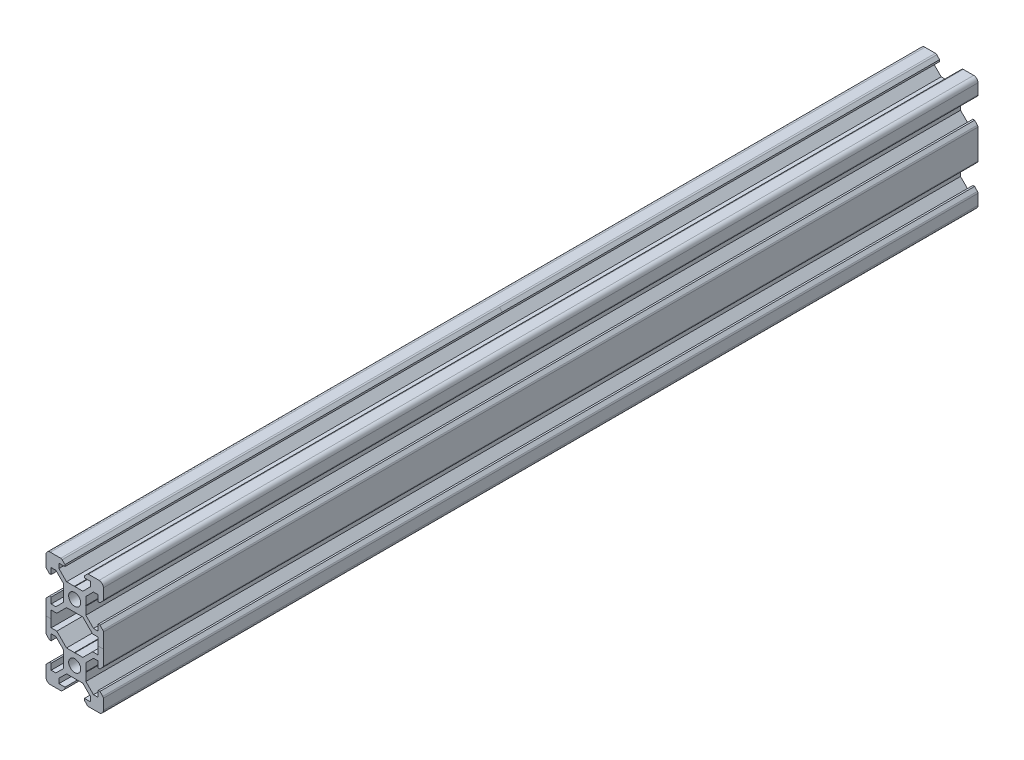
SolidWorks part; units mm, degrees
material "6063-T5"
ref_plane "Front" through (0, 0, 0) normal (0, 0, 1) x (1, 0, 0)
ref_plane "Top" through (0, 0, 0) normal (0, 1, 0) x (1, 0, 0)
ref_plane "Right" through (0, 0, 0) normal (1, 0, 0) x (0, 0, -1)
sketch "Sketch1" plane through (0, 0, 0) normal (0, 0, 1) x (1, 0, 0)
  line L0 (-8.5, 10) -> (-10, 8.5) construction
  line L1 (-8.5, 10) -> (-4.8628, 10)
  line L2 (-10, 8.5) -> (-10, 4.8628)
  line L4 (10, 8.5) -> (10, 4.8628)
  line L5 (-10, 10) -> (10, -10) construction
  line L6 (-10, -10) -> (10, 10) construction
  line L7 (8.2, -5.5) -> (8.2, -3.3865)
  line L8 (-8.2, -5.5) -> (-8.2, -3.3865)
  line L9 (-5.5, 8.2) -> (-3.3865, 8.2)
  line L10 (-8.2, -12.7) -> (-8.2, -7.3)
  line L11 (-3.9005, 2.8395) -> (-6.561, 5.5)
  line L12 (-6.561, 5.5) -> (-8.2, 5.5)
  line L13 (-2.8395, -3.9005) -> (-0.1, -3.9005)
  line L14 (-3.9005, -2.8395) -> (-3.9005, -0.1)
  line L15 (-2.8395, 3.9005) -> (-0.1, 3.9005)
  line L16 (3.9005, -2.8395) -> (3.9005, -0.1)
  line L17 (-8.2, 3.3865) -> (-8.81, 3.3865)
  line L18 (-8.81, 3.3865) -> (-9.7976, 4.3741)
  line L19 (8.5, 10) -> (10, 8.5) construction
  line L20 (-2.8395, 3.9005) -> (-5.5, 6.561)
  line L21 (-5.5, 6.561) -> (-5.5, 8.2)
  line L22 (-3.3865, 8.2) -> (-3.3865, 8.81)
  line L23 (-3.3865, 8.81) -> (-4.3741, 9.7976)
  line L24 (0, 24.069) -> (0, -33.8154) construction
  line L25 (3.3865, 8.81) -> (4.3741, 9.7976)
  line L26 (3.3865, 8.2) -> (3.3865, 8.81)
  line L27 (5.5, 6.561) -> (5.5, 8.2)
  line L28 (2.8395, 3.9005) -> (5.5, 6.561)
  line L29 (3.3865, 8.2) -> (5.5, 8.2)
  line L30 (4.8628, 10) -> (8.5, 10)
  line L31 (-0.1, 3.9005) -> (0, 3.8005)
  line L32 (0.1, 3.9005) -> (0, 3.8005)
  line L33 (0.1, 3.9005) -> (2.8395, 3.9005)
  line L34 (25.9287, 0) -> (-28.3459, 0) construction
  line L35 (-0.1, -3.9005) -> (0, -3.8005)
  line L36 (0.1, -3.9005) -> (0, -3.8005)
  line L37 (0.1, -3.9005) -> (2.8395, -3.9005)
  line L38 (-3.9005, 0.1) -> (-3.8005, 0)
  line L39 (-3.8005, 0) -> (-3.9005, -0.1)
  line L40 (-3.9005, 0.1) -> (-3.9005, 2.8395)
  line L41 (3.9005, 0.1) -> (3.8005, 0)
  line L42 (3.8005, 0) -> (3.9005, -0.1)
  line L43 (3.9005, 0.1) -> (3.9005, 2.8395)
  line L44 (8.81, 3.3865) -> (9.7976, 4.3741)
  line L45 (8.2, 3.3865) -> (8.81, 3.3865)
  line L46 (6.561, 5.5) -> (8.2, 5.5)
  line L47 (3.9005, 2.8395) -> (6.561, 5.5)
  line L48 (2.8395, -3.9005) -> (5.5, -6.561)
  line L49 (3.9005, -2.8395) -> (6.561, -5.5)
  line L50 (-2.8395, -3.9005) -> (-5.5, -6.561)
  line L51 (-3.9005, -2.8395) -> (-6.561, -5.5)
  line L52 (6.561, -5.5) -> (8.2, -5.5)
  line L53 (-6.561, -5.5) -> (-8.2, -5.5)
  line L54 (-8.81, -3.3865) -> (-9.7976, -4.3741)
  line L55 (-8.2, -3.3865) -> (-8.81, -3.3865)
  line L56 (8.81, -3.3865) -> (9.7976, -4.3741)
  line L57 (8.2, -3.3865) -> (8.81, -3.3865)
  line L58 (8.2, 3.3865) -> (8.2, 5.5)
  line L59 (10, -4.8628) -> (10, -15.1372)
  line L60 (-8.2, 3.3865) -> (-8.2, 5.5)
  line L61 (-10, -4.8628) -> (-10, -15.1372)
  line L62 (-28.3459, -10) -> (-10, -10) construction
  line L63 (-3.9005, -20.1) -> (-3.9005, -22.8395)
  line L64 (-3.9005, -20.1) -> (-3.8005, -20)
  line L65 (-3.8005, -20) -> (-3.9005, -19.9)
  line L66 (3.9005, -20.1) -> (3.9005, -22.8395)
  line L67 (3.9005, -20.1) -> (3.8005, -20)
  line L68 (3.8005, -20) -> (3.9005, -19.9)
  line L69 (6.561, -14.5) -> (8.2, -14.5)
  line L70 (3.9005, -17.1605) -> (6.561, -14.5)
  line L71 (3.9005, -17.1605) -> (3.9005, -19.9)
  line L72 (-3.9005, -17.1605) -> (-3.9005, -19.9)
  line L73 (-3.9005, -17.1605) -> (-6.561, -14.5)
  line L74 (-6.561, -14.5) -> (-8.2, -14.5)
  line L75 (-8.2, -16.6135) -> (-8.81, -16.6135)
  line L76 (-8.81, -16.6135) -> (-9.7976, -15.6259)
  line L77 (8.2, -16.6135) -> (8.81, -16.6135)
  line L78 (8.81, -16.6135) -> (9.7976, -15.6259)
  line L79 (-2.8395, -16.0995) -> (-5.5, -13.439)
  line L80 (-2.8395, -16.0995) -> (-0.1, -16.0995)
  line L81 (-0.1, -16.0995) -> (0, -16.1995)
  line L82 (0.1, -16.0995) -> (0, -16.1995)
  line L83 (0.1, -16.0995) -> (2.8395, -16.0995)
  line L84 (2.8395, -16.0995) -> (5.5, -13.439)
  line L85 (-8.2, -16.6135) -> (-8.2, -14.5)
  line L86 (8.2, -16.6135) -> (8.2, -14.5)
  line L87 (2.8395, -23.9005) -> (5.5, -26.561)
  line L88 (-2.8395, -23.9005) -> (-5.5, -26.561)
  line L89 (-0.1, -23.9005) -> (0, -23.8005)
  line L90 (0.1, -23.9005) -> (0, -23.8005)
  line L91 (0.1, -23.9005) -> (2.8395, -23.9005)
  line L92 (-2.8395, -23.9005) -> (-0.1, -23.9005)
  line L93 (-10, -28.5) -> (-10, -24.8628)
  line L94 (10, -28.5) -> (10, -24.8628)
  line L95 (8.81, -23.3865) -> (9.7976, -24.3741)
  line L96 (-8.81, -23.3865) -> (-9.7976, -24.3741)
  line L97 (-8.2, -23.3865) -> (-8.81, -23.3865)
  line L98 (8.2, -23.3865) -> (8.81, -23.3865)
  line L99 (8.2, -23.3865) -> (8.2, -25.5)
  line L100 (-8.2, -23.3865) -> (-8.2, -25.5)
  line L101 (-6.561, -25.5) -> (-8.2, -25.5)
  line L102 (6.561, -25.5) -> (8.2, -25.5)
  line L103 (3.9005, -22.8395) -> (6.561, -25.5)
  line L104 (-3.9005, -22.8395) -> (-6.561, -25.5)
  line L105 (-5.5, -28.2) -> (-3.3865, -28.2)
  line L106 (3.3865, -28.2) -> (5.5, -28.2)
  line L107 (3.3865, -28.2) -> (3.3865, -28.81)
  line L108 (3.3865, -28.81) -> (4.3741, -29.7976)
  line L109 (-3.3865, -28.2) -> (-3.3865, -28.81)
  line L110 (-3.3865, -28.81) -> (-4.3741, -29.7976)
  line L111 (-8.5, -30) -> (-4.8628, -30)
  line L112 (4.8628, -30) -> (8.5, -30)
  line L113 (-5.5, -26.561) -> (-5.5, -28.2)
  line L114 (5.5, -26.561) -> (5.5, -28.2)
  line L115 (-6.239, -7.3) -> (-8.2, -7.3)
  line L116 (-5.5, -6.561) -> (-6.239, -7.3)
  line L117 (6.239, -7.3) -> (8.2, -7.3)
  line L118 (5.5, -6.561) -> (6.239, -7.3)
  line L119 (-6.239, -12.7) -> (-8.2, -12.7)
  line L120 (-5.5, -13.439) -> (-6.239, -12.7)
  line L121 (5.5, -13.439) -> (6.239, -12.7)
  line L122 (6.239, -12.7) -> (8.2, -12.7)
  line L123 (8.2, -12.7) -> (8.2, -7.3)
  line L125 (10, -10) -> (25.9287, -10) construction
  circle A0 centre (0, 0) radius 2.1
  arc A1 (-8.5, 10) -> (-10, 8.5) centre (-8.5, 8.5) ccw
  arc A2 (10, 8.5) -> (8.5, 10) centre (8.5, 8.5) ccw
  arc A3 (-4.3741, 9.7976) -> (-4.8628, 10) centre (-4.8628, 9.3088) ccw
  arc A4 (4.8628, 10) -> (4.3741, 9.7976) centre (4.8628, 9.3088) ccw
  circle A5 centre (0, -20) radius 2.1
  arc A6 (9.7976, 4.3741) -> (10, 4.8628) centre (9.3088, 4.8628) ccw
  arc A7 (-10, 4.8628) -> (-9.7976, 4.3741) centre (-9.3088, 4.8628) ccw
  arc A8 (-10, -4.8628) -> (-9.7976, -4.3741) centre (-9.3088, -4.8628) cw
  arc A9 (9.7976, -4.3741) -> (10, -4.8628) centre (9.3088, -4.8628) cw
  arc A10 (-10, -15.1372) -> (-9.7976, -15.6259) centre (-9.3088, -15.1372) ccw
  arc A11 (9.7976, -15.6259) -> (10, -15.1372) centre (9.3088, -15.1372) ccw
  arc A12 (-10, -24.8628) -> (-9.7976, -24.3741) centre (-9.3088, -24.8628) cw
  arc A13 (9.7976, -24.3741) -> (10, -24.8628) centre (9.3088, -24.8628) cw
  arc A14 (4.8628, -30) -> (4.3741, -29.7976) centre (4.8628, -29.3088) cw
  arc A15 (-4.3741, -29.7976) -> (-4.8628, -30) centre (-4.8628, -29.3088) cw
  arc A16 (-8.5, -30) -> (-10, -28.5) centre (-8.5, -28.5) cw
  arc A17 (10, -28.5) -> (8.5, -30) centre (8.5, -28.5) cw
  point P17 (-9.25, 9.25)
  point P21 (9.25, 9.25)
  dimension "D2" = 4.2
  dimension "D4" = 1.5
  dimension "D3" = 20
  dimension "D5" = 0.529
  dimension "D6" = 6.773
  dimension "D7" = 90
  dimension "D8" = 11
  dimension "D9" = 0.61
  dimension "D10" = 0.1
  dimension "D11" = 0.1
  dimension "D12" = 0.1
  dimension "D13" = 0.1
  dimension "D14" = 5.679
  dimension "D15" = 1.639
  dimension "D16" = 1.8
  dimension "D17" = 90
  dimension "D18" = 6.773
  dimension "D19" = 90
  dimension "D20" = 20
  dimension "D21" = 1.8
extrude "Boss-Extrude2" add sketch "Sketch1" along normal blind 305
sketch "Sketch2" plane through (0, 0, 0) normal (0, 0, -1) x (-1, 0, 0)
  line L0 (-10, -10) -> (10, -10)
  line L1 (-10, -15.1372) -> (-10, -4.8628) construction
  line L2 (10, -4.8628) -> (10, -15.1372) construction
split line "SideFixture1 - SplitLine"
sketch "Sketch3" plane through (0, 0, 305) normal (0, 0, 1) x (1, 0, 0)
  line L0 (-10, -10) -> (10, -10)
  line L1 (-10, -4.8628) -> (-10, -15.1372) construction
  line L2 (10, -15.1372) -> (10, -4.8628) construction
split line "SideFixture2 - SplitLine"
sketch "Sketch4" plane through (0, 10, 0) normal (0, 1, 0) x (1, 0, 0)
  line L0 (-8.5, -152.5) -> (8.5, -152.5)
  line L1 (-8.5, -305) -> (-8.5, 0) construction
  line L2 (8.5, -305) -> (8.5, 0) construction
split line "SideFixture3 - SplitLine"
